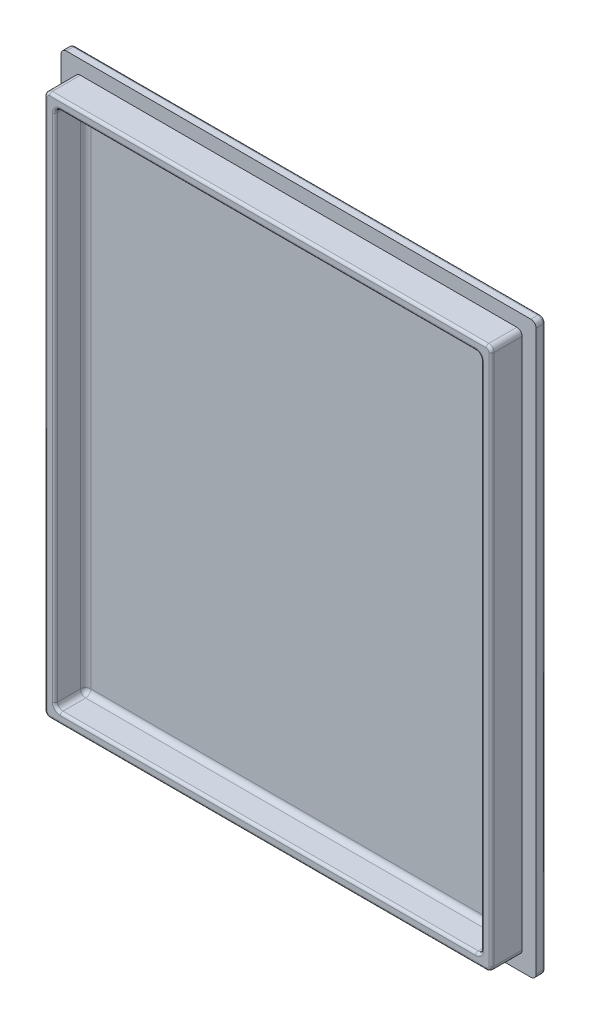
SolidWorks part; units mm, degrees
ref_plane "Front Plane" through (0, 0, 0) normal (0, 0, 1) x (1, 0, 0)
ref_plane "Top Plane" through (0, 0, 0) normal (0, 1, 0) x (1, 0, 0)
ref_plane "Right Plane" through (0, 0, 0) normal (1, 0, 0) x (0, 0, -1)
sketch "Sketch1" plane through (0, 0, 0) normal (0, 0, 1) x (1, 0, 0)
  line L1 (-45, 54) -> (45, 54)
  line L2 (-45, 54) -> (-45, -54)
  line L3 (-45, -54) -> (45, -54)
  line L4 (45, 54) -> (45, -54)
  line L5 (-45, 54) -> (45, -54) construction
  line L6 (-45, -54) -> (45, 54) construction
  point P0 (0, 0)
  dimension "D1" = 108
  dimension "D2" = 90
extrude "Boss-Extrude1" add sketch "Sketch1" along normal blind 1.8
sketch "Sketch2" plane through (0, 0, 1.8) normal (0, 0, 1) x (1, 0, 0)
  line L0 (45, 54) -> (-45, 54) construction
  line L1 (42.35, -51.35) -> (-42.35, -51.35)
  line L2 (42.35, -51.35) -> (42.35, 51.35)
  line L3 (42.35, 51.35) -> (-42.35, 51.35)
  line L4 (-42.35, -51.35) -> (-42.35, 51.35)
  line L5 (42.35, -51.35) -> (-42.35, 51.35) construction
  line L6 (42.35, 51.35) -> (-42.35, -51.35) construction
  line L7 (45, -54) -> (45, 54) construction
  line L9 (40.35, -49.35) -> (-40.35, -49.35)
  line L10 (40.35, -49.35) -> (40.35, 49.35)
  line L11 (40.35, 49.35) -> (-40.35, 49.35)
  line L12 (-40.35, -49.35) -> (-40.35, 49.35)
  line L13 (40.35, -49.35) -> (-40.35, 49.35) construction
  line L14 (40.35, 49.35) -> (-40.35, -49.35) construction
  point P0 (0, 0)
  point P10 (0, 0)
  dimension "D1" = 2.65
  dimension "D2" = 2.65
  dimension "D3" = 2
  dimension "D4" = 2
extrude "Boss-Extrude2" add sketch "Sketch2" along normal blind 5.8
fillet "Fillet1" radius 1 16 edges at (-45, -54, 0.9) (-45, 54, 0.9) (45, -54, 0.9) (40.35, -49.35, 4.7) (40.35, 49.35, 4.7) (-40.35, 49.35, 4.7) (-40.35, -49.35, 4.7) (-42.35, 51.35, 4.7) (42.35, -51.35, 4.7) (-42.35, -51.35, 4.7) (42.35, 51.35, 4.7) (45, 54, 0.9) (0, 49.35, 1.8) (40.35, 0, 1.8) (0, -49.35, 1.8) (-40.35, 0, 1.8)
fillet "Fillet2" radius 0.5 24 edges at (44.7071, -53.7071, 0) (45, 0, 0) (44.7071, 53.7071, 0) (0, 54, 0) (-44.7071, 53.7071, 0) (-45, 0, 0) (-44.7071, -53.7071, 0) (0, -54, 0) (40.0571, -49.0571, 7.6) (40.35, 0, 7.6) (40.0571, 49.0571, 7.6) (0, 49.35, 7.6) (-40.0571, 49.0571, 7.6) (-40.35, 0, 7.6) (-40.0571, -49.0571, 7.6) (0, -49.35, 7.6) (42.0571, 51.0571, 7.6) (42.35, 0, 7.6) (42.0571, -51.0571, 7.6) (0, -51.35, 7.6) (-42.0571, -51.0571, 7.6) (-42.35, 0, 7.6) (-42.0571, 51.0571, 7.6) (0, 51.35, 7.6)
sketch "Sketch3" plane through (0, 0, 0) normal (0, 0, -1) x (-1, 0, 0)
  line L0 (-45, 0) -> (45, 0) construction
  line L1 (-45, -53) -> (-45, 53) construction
  line L2 (45, 53) -> (45, -53) construction
  line L3 (-44.5, 9) -> (44.5, 9) construction
  line L4 (-44.5, 53) -> (-44.5, -53) construction
  line L5 (44.5, -53) -> (44.5, 53) construction
  text T0 "JOULEMETER\r\n100V DC\r\n100A DC" font "Arial Rounded MT Bold" height 7.5
  point P13 (44.5, 12.1257)
  point P14 (0, 0)
  dimension "D1" = 9
extrude "Cut-Extrude1" cut sketch "Sketch3" against normal blind 0.4
